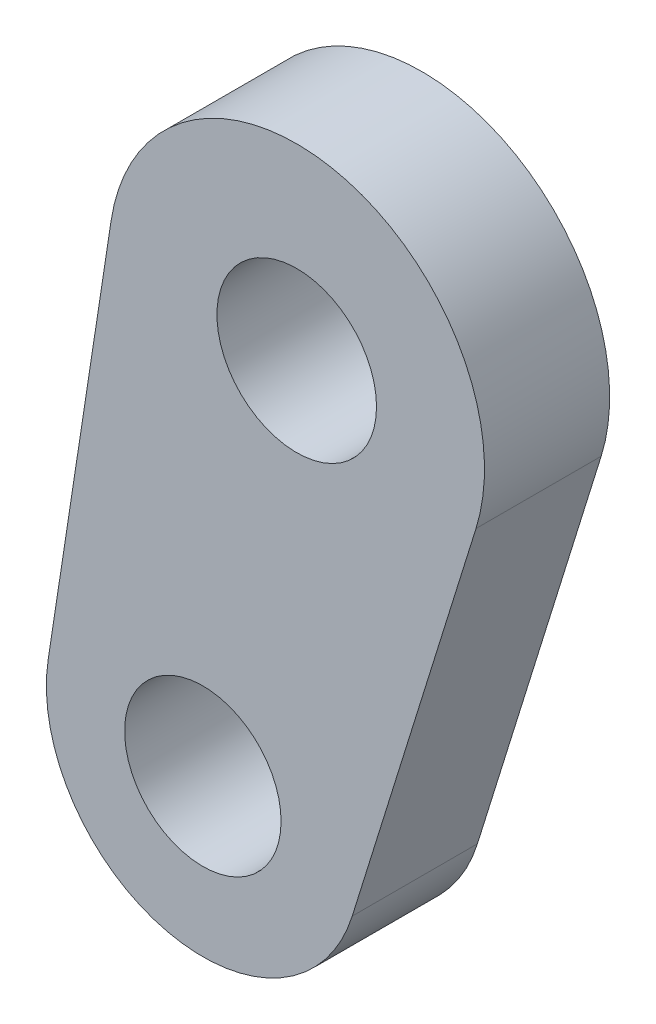
SolidWorks part; units mm, degrees
material "6061-T6 (SS)"
ref_plane "Alzado" through (0, 0, 0) normal (0, 0, 1) x (1, 0, 0)
ref_plane "Planta" through (0, 0, 0) normal (0, 1, 0) x (1, 0, 0)
ref_plane "Vista lateral" through (0, 0, 0) normal (1, 0, 0) x (0, 0, -1)
ref_plane "Plano1" through (0, 0, 44.4) normal (0, 0, 1) x (1, 0, 0)
sketch "Sk_Patilla" plane through (0, 0, 44.4) normal (0, 0, 1) x (1, 0, 0)
  line L0 (3.548, -28.9726) -> (11.4576, -3.5671)
  line L1 (-11.8621, 1.8143) -> (-15.885, -24.4881)
  arc A0 (11.4576, -3.5671) -> (-11.8621, 1.8143) centre (0, 0) ccw
  arc A1 (-15.885, -24.4881) -> (3.548, -28.9726) centre (-6, -26) ccw
  circle A2 centre (0, 0) radius 5.1
  circle A3 centre (-6, -26) radius 5
extrude "Patilla" add sketch "Sk_Patilla" along normal blind 8
